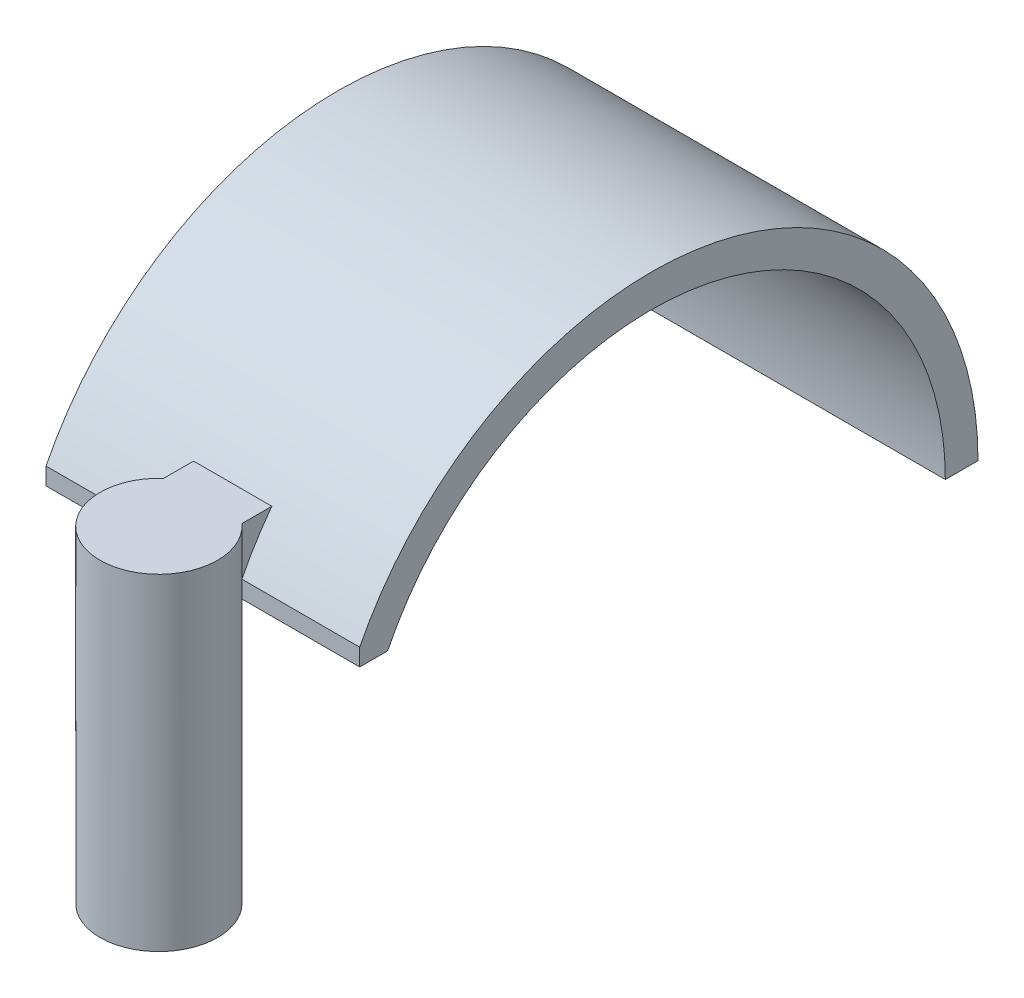
SolidWorks part; units mm, degrees
ref_plane "Front Plane" through (0, 0, 0) normal (0, 0, 1) x (1, 0, 0)
ref_plane "Top Plane" through (0, 0, 0) normal (0, 1, 0) x (1, 0, 0)
ref_plane "Right Plane" through (0, 0, 0) normal (1, 0, 0) x (0, 0, -1)
sketch "Sketch1" plane through (0, 0, 0) normal (0, 1, 0) x (1, 0, 0)
  line L0 (-3.8015, -2.54) -> (3.8015, -2.54)
  circle A0 centre (0, 0) radius 4.572
  circle A1 centre (0, 0) radius 5.715
  dimension "D1" = 9.144
  dimension "D2" = 11.43
  dimension "D3" = 2.54
extrude "Boss-Extrude1" add sketch "Sketch1" along normal blind 25.4 contours L0 A0 | A1 A0
sketch "Sketch2" plane through (0, 25.4, 0) normal (0, 1, 0) x (1, 0, 0)
  line L1 (-3.8015, -2.54) -> (3.8015, -2.54)
  line L2 (-3.8015, -2.54) -> (-3.8015, 32.5906)
  line L3 (-3.8015, 32.5906) -> (3.8015, 32.5906)
  line L4 (3.8015, -2.54) -> (3.8015, 32.5906)
  circle A0 centre (0, 0) radius 5.715
  line M1 (3.8015, -2.54) -> (-3.8015, -2.54)
  arc M2 (-3.8015, -2.54) -> (3.8015, -2.54) centre (0, 0) cw
  circle M3 centre (0, 0) radius 5.715
extrude "Boss-Extrude3" add sketch "Sketch2" along normal blind 6.35 contours L4 L2 M2 M1 M3 | L4 L2 M1 M2 | L4 L3 L2 M3 | L4 L2 M2 M3 | L2 M2 | L4 M2
sketch "Sketch4" plane through (-3.8015, 0, 0) normal (-1, 0, 0) x (0, 0, 1)
  line L0 (-61.1656, 12.723) -> (-64.3406, 12.723)
  line L1 (-4.0156, 12.723) -> (-0.8406, 12.723)
  circle A0 centre (-32.5906, 12.723) radius 31.75
  circle A1 centre (-32.5906, 12.723) radius 28.575
  point P7 (-29.9244, 12.723)
  line M2 (-32.5906, 25.4) -> (-4.2673, 25.4)
  line M3 (-4.2673, 25.4) -> (-4.2673, 31.75)
  line M4 (-4.2673, 31.75) -> (-32.5906, 31.75)
  dimension "D1" = 63.5
  dimension "D2" = 57.15
extrude "Boss-Extrude4" add sketch "Sketch4" against normal blind 19.05 and the other way blind 11.43 contours A1 A0 L0 M4 | A1 A0 M2 M3 M4
sketch "Sketch5" plane through (-3.8015, 0, 0) normal (-1, 0, 0) x (0, 0, 1)
  circle A0 centre (-32.5906, 12.723) radius 28.575
  arc A1 (-6.9816, 25.4) -> (-61.1656, 12.723) centre (-32.5906, 12.723) ccw construction
extrude "Cut-Extrude1" cut sketch "Sketch5" against normal blind 19.05
